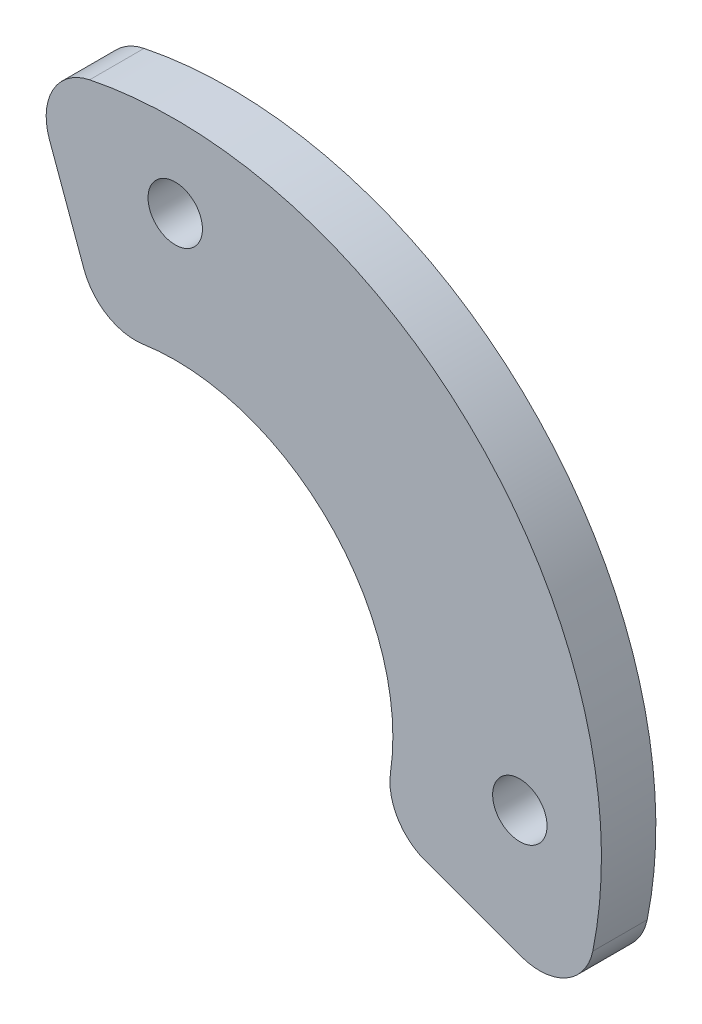
SolidWorks part; units mm, degrees
ref_plane "前视基准面" through (0, 0, 0) normal (0, 0, 1) x (1, 0, 0)
ref_plane "上视基准面" through (0, 0, 0) normal (0, 1, 0) x (1, 0, 0)
ref_plane "右视基准面" through (0, 0, 0) normal (1, 0, 0) x (0, 0, -1)
other "Configuration Table"
sketch "草图1" plane through (0, 0, 0) normal (0, 0, 1) x (1, 0, 0)
  line L0 (0, 0) -> (-8.0375, 22.0828)
  line L1 (0, 0) -> (22.0828, -8.0375)
  line L2 (0, 19) -> (0, 0) construction
  line L3 (19, 0) -> (0, 0) construction
  circle A0 centre (0, 19) radius 1.5
  circle A1 centre (19, 0) radius 1.5
  circle A2 centre (0, -19) radius 1.5 construction
  circle A3 centre (-19, 0) radius 1.5 construction
  circle A4 centre (0, 0) radius 12
  circle A5 centre (0, 0) radius 23.5
  point P12 (0, 0)
  dimension "D1" = 3
  dimension "D4" = 24
  dimension "D5" = 47
  dimension "D2" = 19
  dimension "D6" = 20
  dimension "D7" = 20
  dimension "D3" = 4
extrude "凸台-拉伸1" add sketch "草图1" along normal blind 3 contours L1 A5 L0 A4 A0 A1
fillet "圆角1" radius 3 4 edges at (22.0828, -8.0375, 1.5) (11.2763, -4.1042, 1.5) (-8.0375, 22.0828, 1.5) (-4.1042, 11.2763, 1.5)
